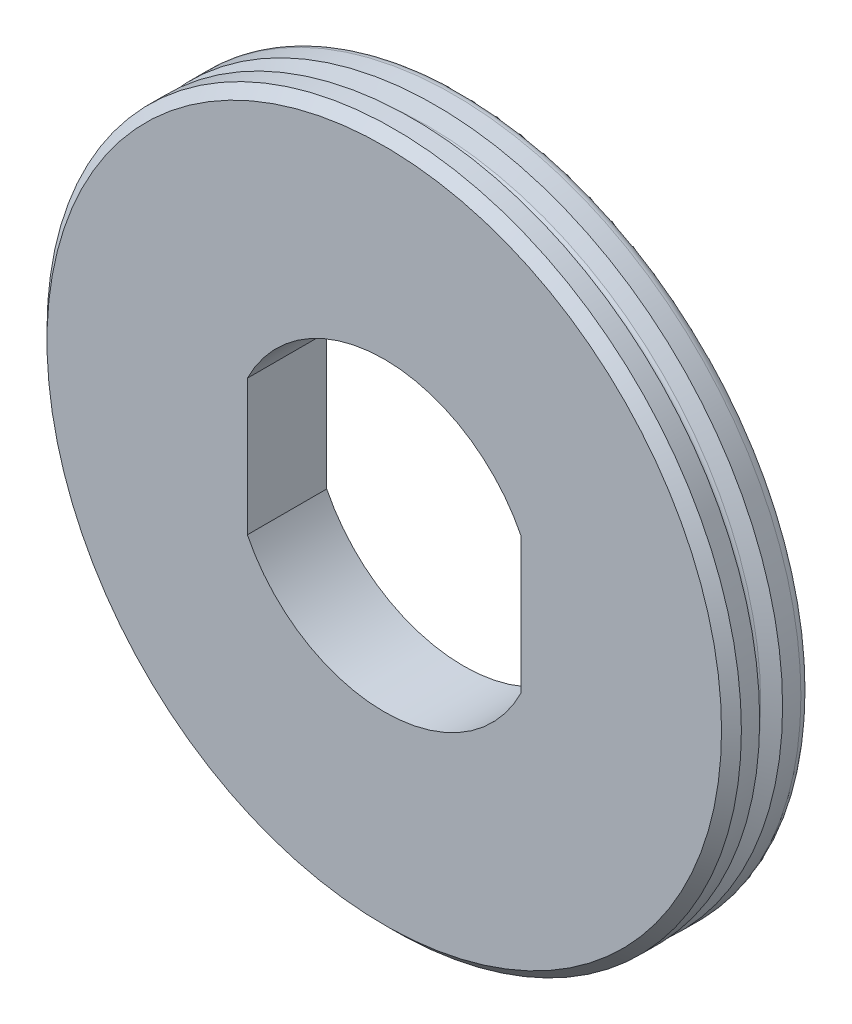
SolidWorks part; units mm, degrees
material "AISI 304"
ref_plane "Спереди" through (0, 0, 0) normal (0, 0, 1) x (1, 0, 0)
ref_plane "Сверху" through (0, 0, 0) normal (0, 1, 0) x (1, 0, 0)
ref_plane "Справа" through (0, 0, 0) normal (1, 0, 0) x (0, 0, -1)
sketch "Эскиз1" plane through (0, 0, 0) normal (0, 0, 1) x (1, 0, 0)
  line L2 (6.9, 3.4176) -> (6.9, -3.4176)
  line L4 (-6.9, 3.4176) -> (-6.9, -3.4176)
  circle A0 centre (0, 0) radius 17.5
  arc A1 (-6.9, -3.4176) -> (6.9, -3.4176) centre (0, 0) ccw
  arc A2 (6.9, 3.4176) -> (-6.9, 3.4176) centre (0, 0) ccw
  point P6 (6.9, 0)
  point P8 (-6.9, 0)
  point P9 (0, -7.7)
  point P11 (0, 7.7)
  dimension "D1" = 7.7
  dimension "D2" = 35
  dimension "D3" = 13.8
extrude "Бобышка-Вытянуть2" add sketch "Эскиз1" along normal mid plane 4
sketch "Эскиз2" plane through (0, 0, 0) normal (1, 0, 0) x (0, 0, -1)
  line L0 (-2, 17.5) -> (-2, -17.5) construction
  line L1 (-2, 17.5) -> (-2, -17.5) construction
  line L2 (-0.5774, 17.5) -> (0.5774, 17.5)
  line L3 (0.5774, 17.5) -> (0, 16.5)
  line L4 (0, 16.5) -> (-0.5774, 17.5)
  line L5 (-3.2487, 0) -> (4.3764, 0) construction
  point P5 (0, 17.5)
  dimension "D1" = 1
  dimension "D2" = 60
revolve "Вырез-Повернуть1" cut sketch "Эскиз2" angle 360 about L5
fillet "Скругление1" [suppressed] radius 0.2
chamfer "Фаска1" distance 0.5 angle 45 1 edges at (17.5, 0, 2)
fillet "Скругление2" radius 0.5 1 edges at (17.5, 0, -2)
fillet "Скругление3" radius 0.2 1 edges at (16.5, 0, 0)
